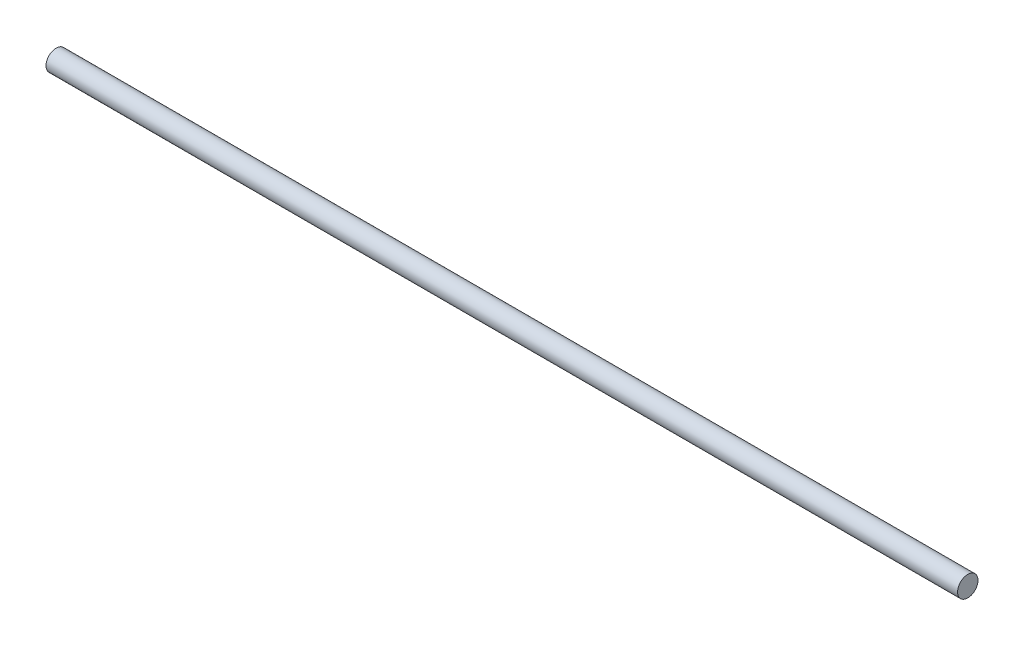
SolidWorks part; units mm, degrees
ref_plane "Front Plane" through (0, 0, 0) normal (0, 0, 1) x (1, 0, 0)
ref_plane "Top Plane" through (0, 0, 0) normal (0, 1, 0) x (1, 0, 0)
ref_plane "Right Plane" through (0, 0, 0) normal (1, 0, 0) x (0, 0, -1)
sketch "Sketch1" plane through (0, 0, 0) normal (1, 0, 0) x (0, 0, -1)
  circle A0 centre (0, 0) radius 4
  dimension "D1" = 8
extrude "Boss-Extrude1" add sketch "Sketch1" along normal mid plane 357
